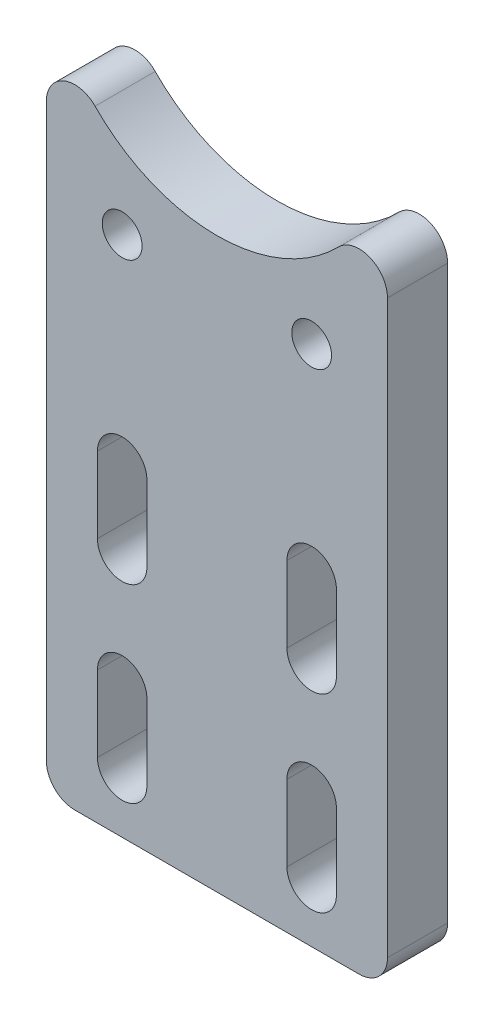
SolidWorks part; units mm, degrees
ref_plane "Front" through (0, 0, 0) normal (0, 0, 1) x (1, 0, 0)
ref_plane "Top" through (0, 0, 0) normal (0, 1, 0) x (1, 0, 0)
ref_plane "Right" through (0, 0, 0) normal (1, 0, 0) x (0, 0, -1)
sketch "Sketch1" plane through (0, 0, 0) normal (0, 0, 1) x (1, 0, 0)
  line L0 (0, -18) -> (0, -78) construction
  line L3 (18, 0) -> (18, -78)
  line L4 (18, -78) -> (-18, -78)
  line L5 (-18, 0) -> (-18, -78)
  line L6 (18, 0) -> (-18, -78) construction
  line L7 (18, -78) -> (-18, 0) construction
  arc A0 (-18, 0) -> (18, 0) centre (0, 0) ccw
  point P9 (0, -39)
  dimension "D1" = 36
  dimension "D2" = 36
  dimension "D3" = 60
extrude "Boss-Extrude1" add sketch "Sketch1" along normal blind 6.35
fillet "Fillet1" radius 3 4 edges at (18, 0, 3.175) (-18, 0, 3.175) (-18, -78, 3.175) (18, -78, 3.175)
sketch "Sketch2" plane through (0, 0, 6.35) normal (0, 0, 1) x (1, 0, 0)
  line L0 (-10, -72) -> (-10, -64) construction
  line L1 (-12.61, -72) -> (-12.61, -64)
  line L2 (-7.39, -72) -> (-7.39, -64)
  line L3 (-10, -52) -> (-10, -44) construction
  line L4 (-12.61, -52) -> (-12.61, -44)
  line L5 (-7.39, -52) -> (-7.39, -44)
  line L6 (-15, -78) -> (15, -78) construction
  line L7 (-18, -14.6969) -> (-18, -75) construction
  line L8 (0, -18) -> (0, -78) construction
  line L9 (10, -72) -> (10, -64) construction
  line L10 (12.61, -72) -> (12.61, -64)
  line L11 (7.39, -72) -> (7.39, -64)
  line L12 (10, -52) -> (10, -44) construction
  line L13 (12.61, -52) -> (12.61, -44)
  line L14 (7.39, -52) -> (7.39, -44)
  arc A0 (-12.61, -72) -> (-7.39, -72) centre (-10, -72) ccw
  arc A1 (-7.39, -64) -> (-12.61, -64) centre (-10, -64) ccw
  arc A2 (-12.61, -52) -> (-7.39, -52) centre (-10, -52) ccw
  arc A3 (-7.39, -44) -> (-12.61, -44) centre (-10, -44) ccw
  arc A4 (-12.8571, -12.5974) -> (12.8571, -12.5974) centre (0, 0) ccw construction
  arc A5 (12.61, -72) -> (7.39, -72) centre (10, -72) cw
  arc A6 (7.39, -64) -> (12.61, -64) centre (10, -64) cw
  arc A7 (12.61, -52) -> (7.39, -52) centre (10, -52) cw
  arc A8 (7.39, -44) -> (12.61, -44) centre (10, -44) cw
  point P2 (-10, -68)
  point P7 (-10, -48)
  point P25 (10, -68)
  point P32 (10, -48)
  dimension "D4" = 5.22
  dimension "D1" = 10
  dimension "D2" = 8
  dimension "D3" = 8
  dimension "D5" = 20
extrude "Cut-Extrude1" cut sketch "Sketch2" against normal up to next
sketch "Sketch3" plane through (0, 0, 6.35) normal (0, 0, 1) x (1, 0, 0)
  line L0 (10, -44) -> (10, -22.9129) construction
  line L1 (-10, -44) -> (-10, -22.9129) construction
  circle A0 centre (0, 0) radius 25 construction
  dimension "D1" = 50
hole_wizard "Tap Drill for M5x0.8 Tap1" positions "3DSketch1" profile "Sketch4" hole size "M5x0.8" standard "ANSI Metric" end condition up to next
sketch3d "3DSketch1"
  point P0 (-10, -22.9129, 6.35)
  point P3 (10, -22.9129, 6.35)
sketch "Sketch4" plane through (-10, -22.9129, 6.35) normal (1, 0, 0) x (0, -1, 0)
  line L0 (0, 0) -> (0, 6.35)
  line L1 (0, 6.35) -> (2.1, 6.35)
  line L2 (2.1, 6.35) -> (2.1, 0)
  line L5 (2.1, 0) -> (0, 0)
  line L11 (0, -6.35) -> (0, 107.95) construction
  dimension "Thru Hole Dia." = 4.2
  dimension "Thru Hole Depth" = 6.35
